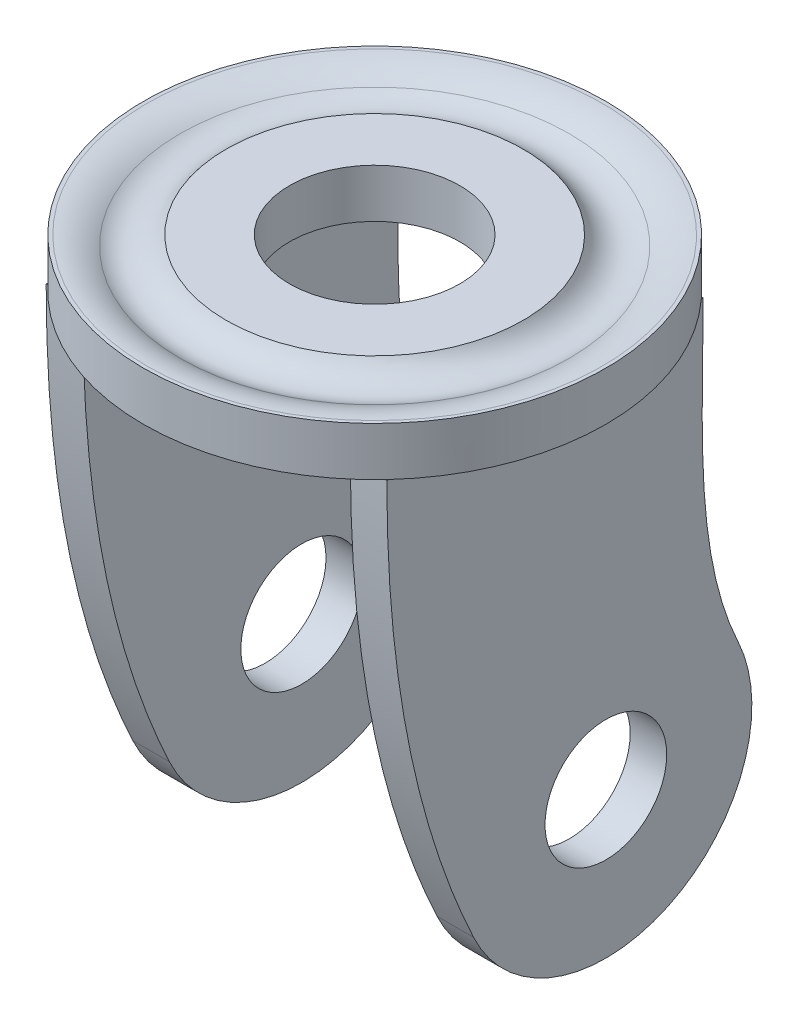
SolidWorks part; units mm, degrees
ref_plane "Front Plane" through (0, 0, 0) normal (0, 0, 1) x (1, 0, 0)
ref_plane "Top Plane" through (0, 0, 0) normal (0, 1, 0) x (1, 0, 0)
ref_plane "Right Plane" through (0, 0, 0) normal (1, 0, 0) x (0, 0, -1)
sketch "Sketch1" plane through (0, 0, 0) normal (0, 0, 1) x (1, 0, 0)
  line L0 (0, 8.3692) -> (0, 0) construction
  line L1 (-16.8, 4) -> (-19, 4)
  line L2 (-7, 0) -> (-19, 0)
  line L3 (-7, 0) -> (-7, 4)
  line L4 (-7, 4) -> (-12.2, 4)
  line L5 (-19, 0) -> (-19, 4)
  arc A1 (-12.2, 4) -> (-16.8, 4) centre (-14.5, 5.5075) cw
  dimension "D1" = 2.75
  dimension "D2" = 4
  dimension "D3" = 12
  dimension "D4" = 7
  dimension "D5" = 5.2
  dimension "D6" = 2.2
revolve "Revolve1" add sketch "Sketch1" angle 360 about L0
sketch "Sketch2" plane through (0, 0, 0) normal (1, 0, 0) x (0, 0, -1)
  line L0 (0, 0) -> (0, 11.7727) construction
  line L1 (13, 0) -> (-13, 0)
  line L2 (-19, 0) -> (19, 0) construction
  line L3 (-19, 4) -> (-19, 0) construction
  line L5 (15.8757, -25.9286) -> (-5.8757, -36.0714) construction
  line L6 (13, 10.435) -> (13, -10.435) construction
  line L7 (-13, 14.7073) -> (-13, -14.7073) construction
  arc A0 (15.8757, -25.9286) -> (-5.8757, -36.0714) centre (5, -31) cw
  circle A1 centre (5, -31) radius 5
  spline S0 degree 3 poles (-5.8757, -36.0714) (-11.2481, -24.5503) (-13, -12.2561) (-13, 0) knots 0 0 0 0 1 1 1 1
  spline S1 degree 3 poles (15.8757, -25.9286) (12.1561, -17.952) (13, -8.6959) (13, 0) knots 0 0 0 0 1 1 1 1
  point P7 (0, 0)
  point P10 (5, -31)
  dimension "D6" = 10
  dimension "D1" = 6
  dimension "D2" = 25
  dimension "D3" = 31
  dimension "D4" = 24
  dimension "D5" = 5
extrude "Boss-Extrude1" add sketch "Sketch2" against normal blind 3 from offset 11 offset against normal yes
mirror "Mirror1" about plane through (0, 0, 0) normal (1, 0, 0) of "Boss-Extrude1"
fillet "Fillet1" radius 5 1 edges at (0, 4, 16.8)
